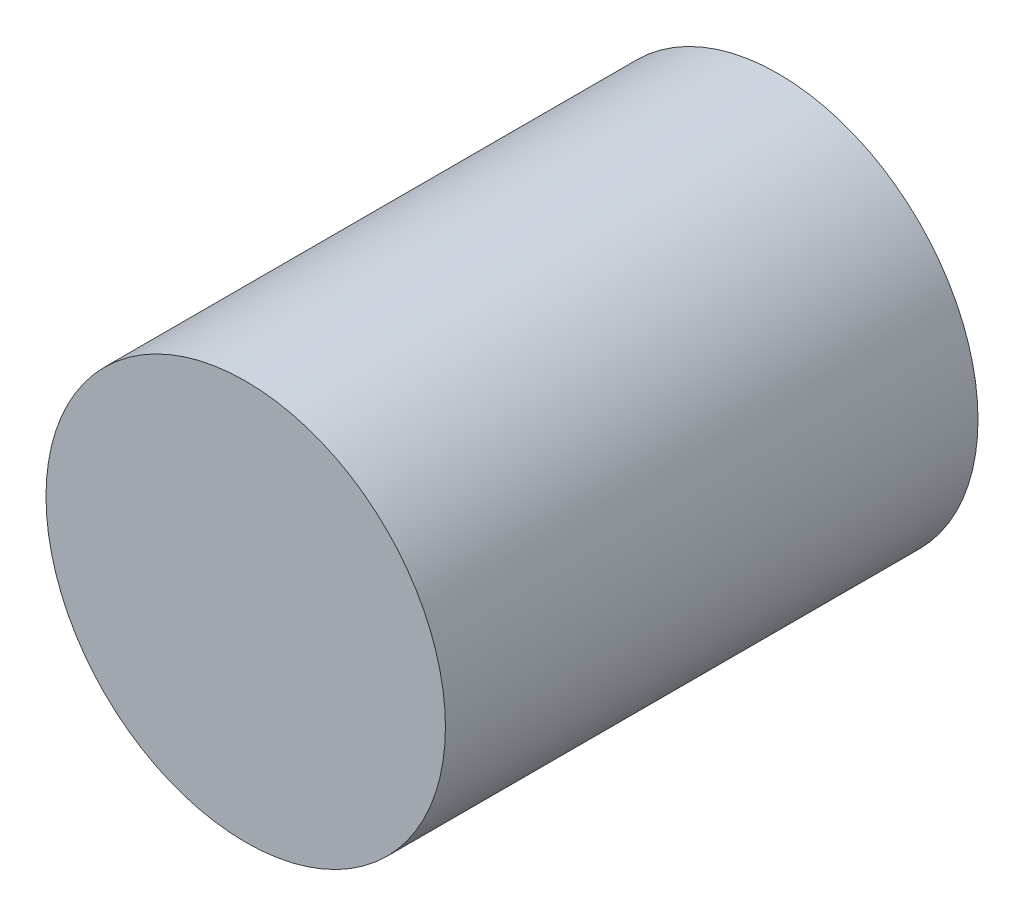
SolidWorks part; units mm, degrees
ref_plane "Front Plane" through (0, 0, 0) normal (0, 0, 1) x (1, 0, 0)
ref_plane "Top Plane" through (0, 0, 0) normal (0, 1, 0) x (1, 0, 0)
ref_plane "Right Plane" through (0, 0, 0) normal (1, 0, 0) x (0, 0, -1)
sketch "Sketch1" plane through (0, 0, 0) normal (0, 0, 1) x (1, 0, 0)
  circle A0 centre (0, 0) radius 30
extrude "Cylinder" add sketch "Sketch1" along normal blind 80
